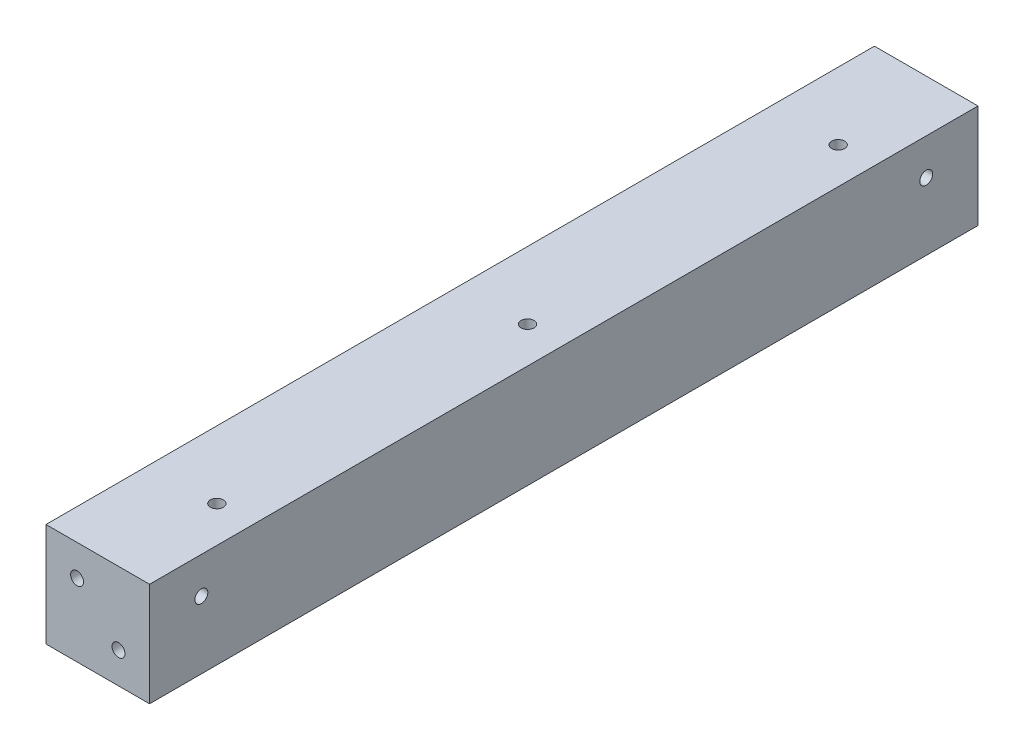
SolidWorks part; units mm, degrees
ref_plane "Ön Düzlem" through (0, 0, 0) normal (0, 0, 1) x (1, 0, 0)
ref_plane "Üst Düzlem" through (0, 0, 0) normal (0, 1, 0) x (1, 0, 0)
ref_plane "Sağ Düzlem" through (0, 0, 0) normal (1, 0, 0) x (0, 0, -1)
sketch "Çizim1" plane through (0, 0, 0) normal (0, 0, 1) x (1, 0, 0)
  line L0 (0, 20) -> (20, 0) construction
  line L1 (0, 0) -> (20, 0)
  line L2 (0, 0) -> (0, 20)
  line L3 (0, 20) -> (20, 20)
  line L4 (20, 0) -> (20, 20)
  line L5 (20, 20) -> (0, 0) construction
  point P4 (10, 10)
extrude "Yükseklik-Ekstrüzyon1" add sketch "Çizim1" along normal blind 160
sketch "Çizim2" plane through (0, 0, 0) normal (-1, 0, 0) x (0, 0, 1)
  line L0 (20, 0) -> (20, 20) construction
  line L1 (160, 0) -> (0, 0) construction
  line L2 (160, 20) -> (0, 20) construction
  line L3 (80, 0) -> (80, 20) construction
  line L4 (140, 0) -> (140, 20) construction
  line L5 (0, 20) -> (0, 0) construction
  line L6 (160, 20) -> (160, 0) construction
  line L7 (0, 7) -> (160, 7) construction
  point P16 (20, 7)
  point P17 (80, 7)
  point P18 (140, 7)
  dimension "D1" = 20
  dimension "D2" = 20
  dimension "D3" = 7
sketch "Çizim4" plane through (0, 20, 0) normal (0, 1, 0) x (1, 0, 0)
  line L0 (13, 0) -> (13, -160) construction
  line L1 (20, 0) -> (0, 0) construction
  line L2 (20, -160) -> (0, -160) construction
  line L3 (20, -160) -> (20, 0) construction
  line L4 (0, -20) -> (20, -20) construction
  line L5 (0, -80) -> (20, -80) construction
  line L6 (0, 0) -> (0, -160) construction
  line L7 (0, -140) -> (20, -140) construction
  point P19 (13, -20)
  point P20 (13, -80)
  point P21 (13, -140)
  dimension "D1" = 7
sketch "Çizim13" plane through (0, 0, 160) normal (0, 0, 1) x (1, 0, 0)
  line L0 (20, 0) -> (20, 20) construction
  line L2 (0, 0) -> (20, 0) construction
  line L4 (0, 0) -> (0, 20) construction
  line L5 (0, 20) -> (20, 20) construction
  circle A0 centre (14, 6) radius 1.25
  circle A1 centre (6, 14) radius 1.25
  dimension "D1" = 6
  dimension "D3" = 6
  dimension "D2" = 6
  dimension "D4" = 6
extrude "Kes-Ekstrüzyon1" cut sketch "Çizim13" against normal blind 10
cosmetic thread "Cosmetic Thread1" parameters "D2"=3
cosmetic thread "Cosmetic Thread14" parameters "D2"=3
sketch "Çizim15" plane through (0, 0, 0) normal (0, 0, -1) x (-1, 0, 0)
  line L0 (-20, 0) -> (-20, 20) construction
  line L2 (0, 0) -> (-20, 0) construction
  line L4 (0, 0) -> (0, 20) construction
  line L5 (0, 20) -> (-20, 20) construction
  circle A0 centre (-14, 6) radius 1.25
  circle A1 centre (-6, 14) radius 1.25
  dimension "D1" = 6
  dimension "D3" = 6
  dimension "D4" = 6
  dimension "D2" = 6
extrude "Kes-Ekstrüzyon2" cut sketch "Çizim15" against normal blind 10
cosmetic thread "Cosmetic Thread2" parameters "D2"=3
cosmetic thread "Cosmetic Thread13" parameters "D2"=3
sketch "Çizim18" plane through (20, 0, 0) normal (1, 0, 0) x (0, 0, -1)
  line L0 (0, 0) -> (0, 20) construction
  line L1 (0, 20) -> (-160, 20) construction
  line L2 (-160, 0) -> (-160, 20) construction
  circle A0 centre (-10, 13) radius 1.25
  circle A1 centre (-150, 13) radius 1.25
  dimension "D1" = 10
  dimension "D2" = 7
  dimension "D3" = 10
  dimension "D4" = 7
extrude "Kes-Ekstrüzyon3" cut sketch "Çizim18" against normal blind 10
cosmetic thread "Cosmetic Thread11" parameters "D2"=3
cosmetic thread "Cosmetic Thread12" parameters "D2"=3
sketch "Çizim20" plane through (0, 0, 0) normal (0, -1, 0) x (1, 0, 0)
  line L0 (0, 0) -> (0, 160) construction
  line L1 (0, 0) -> (20, 0) construction
  line L2 (0, 160) -> (20, 160) construction
  circle A0 centre (7, 10) radius 1.25
  circle A1 centre (7, 150) radius 1.25
  dimension "D1" = 7
  dimension "D2" = 10
  dimension "D3" = 7
  dimension "D4" = 10
extrude "Kes-Ekstrüzyon4" cut sketch "Çizim20" against normal blind 10
cosmetic thread "Cosmetic Thread9" parameters "D2"=3
cosmetic thread "Cosmetic Thread10" parameters "D2"=3
sketch "Sketch1" plane through (0, 20, 0) normal (0, 1, 0) x (1, 0, 0)
  circle A0 centre (13, -20) radius 1.25
  circle A1 centre (13, -80) radius 1.25
  circle A2 centre (13, -140) radius 1.25
extrude "Cut-Extrude1" cut sketch "Sketch1" against normal blind 10
cosmetic thread "Cosmetic Thread6" parameters "D2"=3
cosmetic thread "Cosmetic Thread7" parameters "D2"=3
cosmetic thread "Cosmetic Thread8" parameters "D2"=3
sketch "Sketch2" plane through (0, 0, 0) normal (-1, 0, 0) x (0, 0, 1)
  circle A0 centre (20, 7) radius 1.25
  circle A1 centre (80, 7) radius 1.25
  circle A2 centre (140, 7) radius 1.25
extrude "Cut-Extrude2" cut sketch "Sketch2" against normal blind 10
cosmetic thread "Cosmetic Thread3" parameters "D2"=3
cosmetic thread "Cosmetic Thread4" parameters "D2"=3
cosmetic thread "Cosmetic Thread5" parameters "D2"=3
